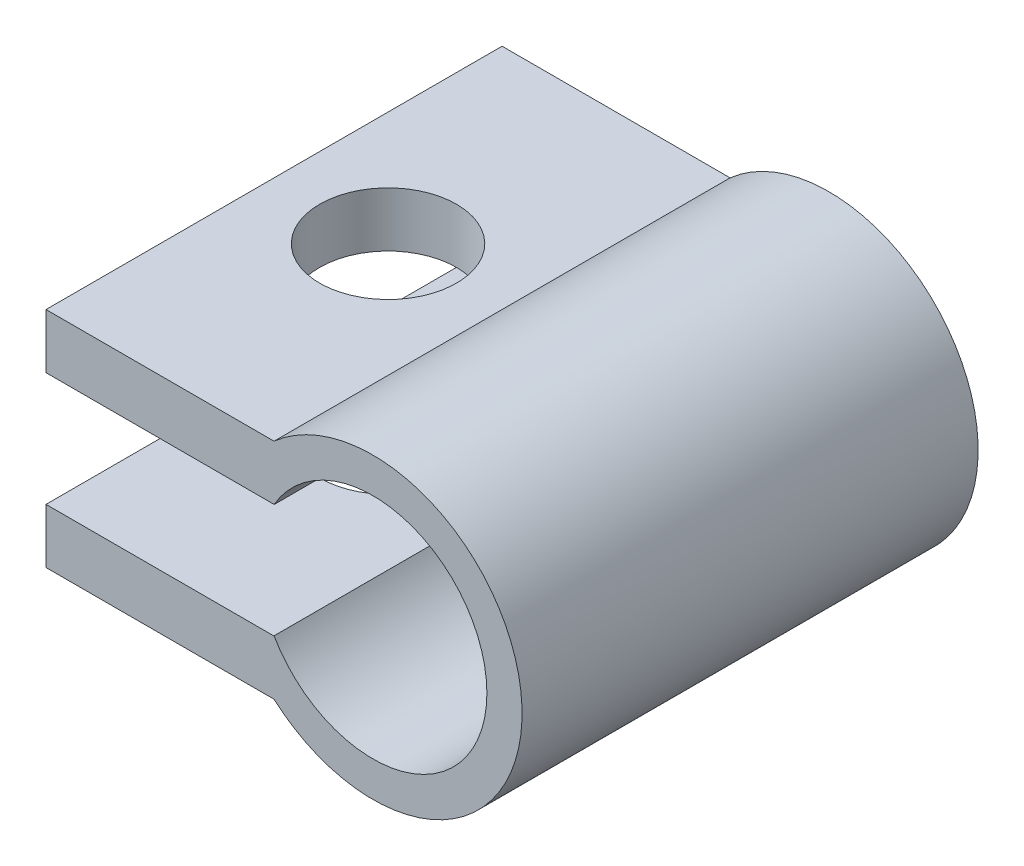
SolidWorks part; units mm, degrees
ref_plane "Front Plane" through (0, 0, 0) normal (0, 0, 1) x (1, 0, 0)
ref_plane "Top Plane" through (0, 0, 0) normal (0, 1, 0) x (1, 0, 0)
ref_plane "Right Plane" through (0, 0, 0) normal (1, 0, 0) x (0, 0, -1)
sketch "Sketch1" plane through (0, 0, 0) normal (0, 0, 1) x (1, 0, 0)
  line L1 (-7.1673, 1.25) -> (-7.1673, 2.45)
  line L4 (-7.1673, -1.25) -> (-7.1673, -2.45)
  line L6 (-15.4481, 0) -> (7.1413, 0) construction
  line L7 (-2.1673, 1.246) -> (-2.1673, 1.25)
  line L8 (-2.1673, 1.25) -> (-7.1673, 1.25)
  line L9 (-2.1673, -1.246) -> (-2.1673, -1.25)
  line L10 (-2.1673, -1.25) -> (-7.1673, -1.25)
  line L11 (-7.1673, 2.45) -> (-2.1673, 2.45)
  line L12 (-7.1673, -2.45) -> (-2.1673, -2.45)
  line L13 (-2.1673, 2.45) -> (-2.1673, -2.45) construction
  arc A2 (-2.1673, 2.45) -> (-2.1673, -2.45) centre (0, 0) cw
  arc A5 (-2.1673, 1.246) -> (-2.1673, -1.246) centre (0, 0) cw
  point P2 (-2.1673, 1.25)
  point P3 (0, 0)
  point P16 (-2.1673, 2.45)
  dimension "D1" = 1.2
  dimension "D2" = 2.5
  dimension "D4" = 3.2711
  dimension "D3" = 2.5
  dimension "D6" = 5
extrude "Boss-Extrude1" add sketch "Sketch1" along normal mid plane 10
sketch "Sketch2" plane through (0, 2.45, 0) normal (0, 1, 0) x (1, 0, 0)
  line L0 (-7.1673, 0) -> (0, 0) construction
  line L1 (-7.1673, -5) -> (-7.1673, 5) construction
  circle A0 centre (-4.6673, 0) radius 1.5
  point P7 (0, 0)
  point P14 (-2.7726, 0)
  point P17 (-5.2577, 0)
  point P18 (-5.0746, 0)
  dimension "D1" = 3
  dimension "D3" = 2.5
extrude "Cut-Extrude1" cut sketch "Sketch2" against normal blind 10
